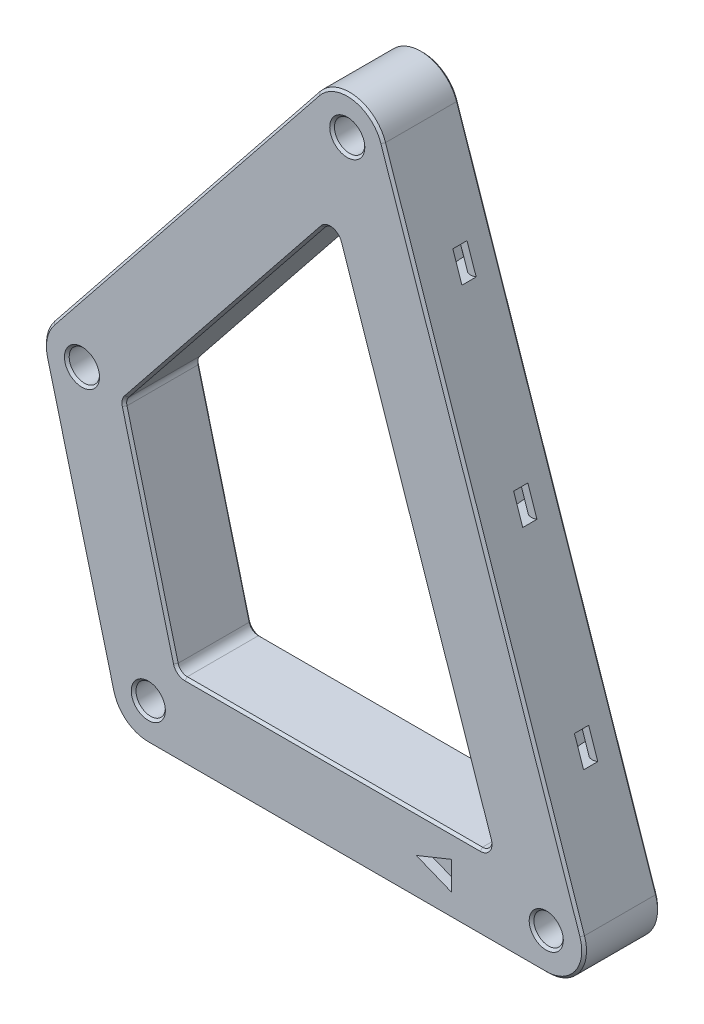
SolidWorks part; units mm, degrees
ref_plane "Płaszczyzna przednia" through (0, 0, 0) normal (0, 0, 1) x (1, 0, 0)
ref_plane "Płaszczyzna górna" through (0, 0, 0) normal (0, 1, 0) x (1, 0, 0)
ref_plane "Płaszczyzna prawa" through (0, 0, 0) normal (1, 0, 0) x (0, 0, -1)
sketch "Szkic1" plane through (0, 0, 0) normal (0, 0, 1) x (1, 0, 0)
  line L0 (-21, -62) -> (21, -62) construction
  line L1 (0, -62) -> (0, 0) construction
  line L2 (-21, -62) -> (-28, -35) construction
  line L3 (-28, -35) -> (0, 0) construction
  line L4 (0, 0) -> (21, -62) construction
  line L5 (-32.3746, -34.0651) -> (1.4433, 8.2073)
  line L6 (1.4433, 8.2073) -> (26.5781, -66)
  line L7 (-24.0952, -66) -> (26.5781, -66)
  line L8 (-24.0952, -66) -> (-32.3746, -34.0651)
  line L9 (-23.6254, -35.9349) -> (-1.4433, -8.2073)
  line L10 (-1.4433, -8.2073) -> (15.4219, -58)
  line L11 (-17.9048, -58) -> (15.4219, -58)
  line L12 (-17.9048, -58) -> (-23.6254, -35.9349)
  circle A0 centre (-21, -62) radius 1.55
  circle A1 centre (21, -62) radius 1.55
  circle A2 centre (0, 0) radius 1.6
  circle A3 centre (-28, -35) radius 1.6
  point P0 (0, 0)
  point P1 (-28, -35)
  point P3 (-21, -62)
  point P4 (21, -62)
  dimension "D5" = 3.2
  dimension "D6" = 3.1
  dimension "D1" = 28
  dimension "D2" = 35
  dimension "D3" = 42
  dimension "D4" = 62
  dimension "D7" = 4
  dimension "D8" = 4
extrude "Dodanie-wyciągnięcie1" add sketch "Szkic1" along normal blind 8
fillet "Zaokrąglenie1" radius 4 4 edges at (-24.0952, -66, 4) (-32.3746, -34.0651, 4) (26.5781, -66, 4) (1.4433, 8.2073, 4)
sketch "Szkic2" plane through (0, 0, 0) normal (0, 0, 1) x (1, 0, 0)
  circle A0 centre (0, 0) radius 3
  circle A1 centre (-28, -35) radius 3
  circle A2 centre (-21, -62) radius 3
  circle A3 centre (21, -62) radius 3
  dimension "D1" = 6
extrude "Wytnij-wyciągnięcie1" cut sketch "Szkic2" along normal blind 3
fillet "Zaokrąglenie2" radius 1 4 edges at (15.4219, -58, 4) (-17.9048, -58, 4) (-23.6254, -35.9349, 4) (-1.4433, -8.2073, 4)
chamfer "Sfazowanie1" distance 0.25 angle 45 36 edges at (7.0588, -33.3087, 0) (-1.631, -9.2742, 0) (14.8401, -57.5827, 0) (-12.9488, -22.5891, 0) (-1.5518, -58, 0) (-23.5097, -35.9596, 0) (-17.743, -57.7909, 0) (-20.7994, -46.8352, 0) (7.0588, -33.3087, 8) (-1.631, -9.2742, 8) (14.8401, -57.5827, 8) (-12.9488, -22.5891, 8) (-1.5518, -58, 8) (-23.5097, -35.9596, 8) (-17.743, -57.7909, 8) (-20.7994, -46.8352, 8) (14.2886, -29.7168, 8) (0.6928, 3.9395, 8) (24.2506, -64.331, 8) (-17.1235, -15.0012, 8) (0, -66, 8) (-31.9117, -34.1641, 8) (-23.4479, -65.1635, 8) (-28.372, -49.5038, 8) (14.2886, -29.7168, 0) (0.6928, 3.9395, 0) (24.2506, -64.331, 0) (-17.1235, -15.0012, 0) (0, -66, 0) (-31.9117, -34.1641, 0) (-23.4479, -65.1635, 0) (-28.372, -49.5038, 0) (-19.45, -62, 8) (22.55, -62, 8) (1.6, 0, 8) (-26.4, -35, 8)
sketch "Szkic3" plane through (0, 0, 8) normal (0, 0, -1) x (-1, 0, 0)
  line L0 (-21, -62) -> (-11, -62) construction
  line L1 (-11, -60.5) -> (-11, -63.5)
  line L2 (-11, -63.5) -> (-7.2919, -62)
  line L3 (-7.2919, -62) -> (-11, -60.5)
  dimension "D1" = 10
  dimension "D2" = 3
  dimension "D3" = 4
extrude "Wytnij-wyciągnięcie2" cut sketch "Szkic3" along normal blind 1
ref_plane "Płaszczyzna1" through (24.7886, -60.7168, 0.25) normal (-0.3208, 0.9471, 0) x (0.9471, 0.3208, 0)
ref_plane "Płaszczyzna2" through (19.9765, -46.5096, 0.25) normal (-0.3208, 0.9471, 0) x (0.9471, 0.3208, 0)
sketch "Szkic4" plane through (19.9765, -46.5096, 0.25) normal (-0.3208, 0.9471, 0) x (0.9471, 0.3208, 0)
  line L0 (-0.25, 0.25) -> (-6.022, 0.25) construction
  line L1 (0, 0) -> (0, -7.5) construction
  line L2 (-4, 0.25) -> (-2.5, 0.25)
  line L3 (0, -2.25) -> (0, -3.75)
  arc A0 (-2.5, 0.25) -> (0, -2.25) centre (0, 0.25) ccw
  arc A1 (-4, 0.25) -> (0, -3.75) centre (0, 0.25) ccw
  dimension "D1" = 2.5
  dimension "D2" = 1.5
extrude "Wytnij-wyciągnięcie3" cut sketch "Szkic4" against normal blind 3
pattern_linear "Szyk liniowy1" count 3 spacing 20 along (-0.3208, 0.9471, 0) of "Wytnij-wyciągnięcie3"
